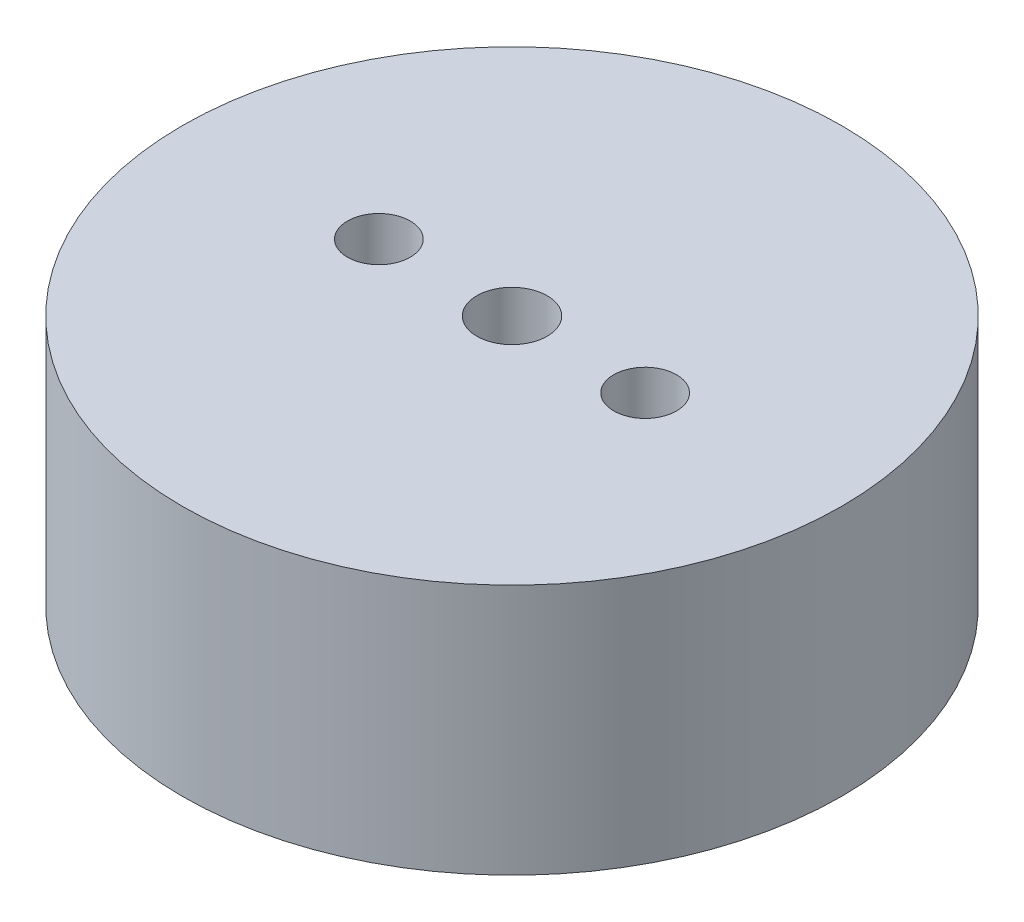
SolidWorks part; units mm, degrees
material "Balsa"
ref_plane "Front Plane" through (0, 0, 0) normal (0, 0, 1) x (1, 0, 0)
ref_plane "Top Plane" through (0, 0, 0) normal (0, 1, 0) x (1, 0, 0)
ref_plane "Right Plane" through (0, 0, 0) normal (1, 0, 0) x (0, 0, -1)
sketch "Sketch1" plane through (0, 0, 0) normal (0, 1, 0) x (1, 0, 0)
  circle A0 centre (0, 0) radius 33.3375
  dimension "D1" = 66.675
extrude "Boss-Extrude1" add sketch "Sketch1" along normal blind 25.4
sketch "Sketch2" plane through (0, 25.4, 0) normal (0, 1, 0) x (1, 0, 0)
  circle A0 centre (0, 0) radius 3.556
  dimension "D1" = 7.112
extrude "Cut-Extrude1" cut sketch "Sketch2" against normal through all
sketch "Sketch3" plane through (0, 25.4, 0) normal (0, 1, 0) x (-1, 0, 0)
  line L0 (0, 0) -> (0, -42.317) construction
  circle A0 centre (13.462, 0) radius 3.175
  circle A1 centre (-13.462, 0) radius 3.175
  dimension "D1" = 6.35
  dimension "D2" = 13.462
extrude "Cut-Extrude2" cut sketch "Sketch3" against normal through all
